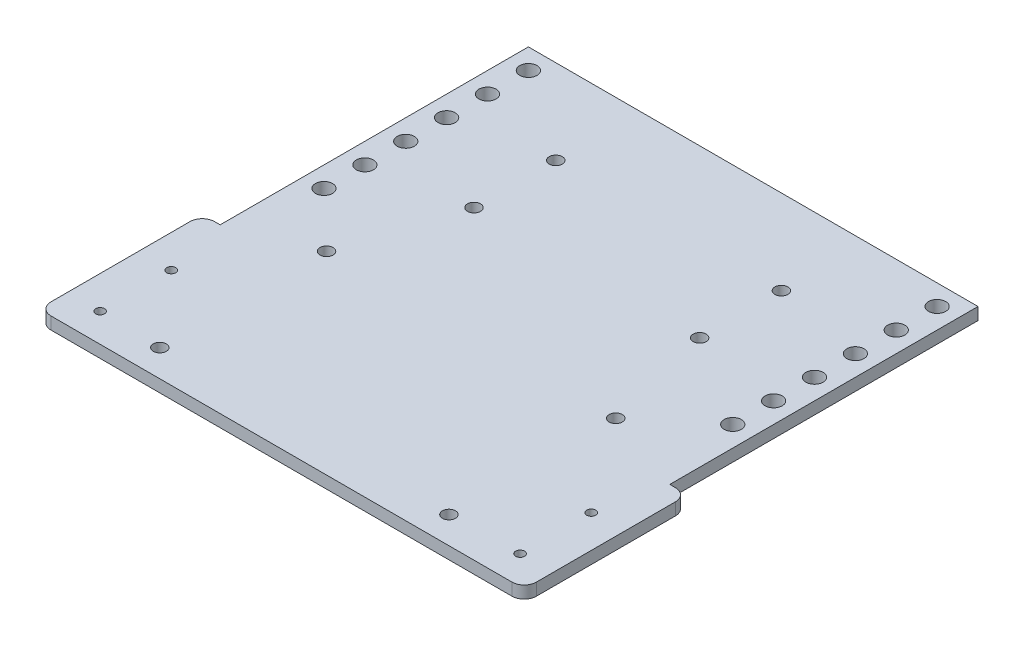
SolidWorks part; units mm, degrees
ref_plane "Alzado" through (0, 0, 0) normal (0, 0, 1) x (1, 0, 0)
ref_plane "Planta" through (0, 0, 0) normal (0, 1, 0) x (1, 0, 0)
ref_plane "Vista lateral" through (0, 0, 0) normal (1, 0, 0) x (0, 0, -1)
sketch "Croquis1" plane through (0, 0, 0) normal (0, 1, 0) x (1, 0, 0)
  line L1 (-95, -57.7) -> (95, -57.7)
  line L2 (-95, -57.7) -> (-95, 57.7)
  line L3 (-95, 57.7) -> (95, 57.7)
  line L4 (95, -57.7) -> (95, 57.7)
  line L5 (0, 57.7) -> (0, -57.7) construction
  line L6 (-95, 0) -> (95, 0) construction
  point P0 (0, 0)
  dimension "D1" = 190
  dimension "D2" = 115.4
extrude "Saliente-Extruir1" add sketch "Croquis1" along normal blind 3
sketch "Croquis2" plane through (0, 3, 0) normal (0, 1, 0) x (1, 0, 0)
  circle A0 centre (-36.375, -51.1) radius 1.6
  circle A1 centre (-36.375, -10.3) radius 1.6
  circle A2 centre (34.375, -10.3) radius 1.6
  circle A3 centre (34.375, -51.1) radius 1.6
  dimension "D1" = 3.2
  dimension "D2" = 3.2
  dimension "D3" = 3.2
  dimension "D4" = 3.2
extrude "Cortar-Extruir1" cut sketch "Croquis2" against normal blind 5
sketch "Croquis4" plane through (0, 3, 0) normal (0, 1, 0) x (1, 0, 0)
  line L0 (-39.375, -54.7) -> (-39.375, -6.7) construction
  line L2 (-95, -57.7) -> (95, -57.7) construction
  line L3 (39.375, -6.7) -> (39.375, -54.7) construction
  circle A0 centre (-51.375, -50.7) radius 1.1
  circle A1 centre (-51.375, -33.3) radius 1.1
  circle A2 centre (51.375, -33.3) radius 1.1
  circle A3 centre (51.375, -50.7) radius 1.1
  dimension "D1" = 17.4
  dimension "D2" = 2.2
  dimension "D3" = 2.2
  dimension "D4" = 12
  dimension "D5" = 7
  dimension "D7" = 12
  dimension "D8" = 12
  dimension "D9" = 17.4
  dimension "D10" = 7
  dimension "D11" = 2.2
  dimension "D12" = 2.2
  dimension "D6" = 12
extrude "Cortar-Extruir3" cut sketch "Croquis4" against normal blind 5
sketch "Croquis5" plane through (0, 3, 0) normal (0, 1, 0) x (1, 0, 0)
  line L1 (-95, -57.7) -> (-59.375, -57.7)
  line L2 (-95, -57.7) -> (-95, -17.7)
  line L3 (-95, -17.7) -> (-59.375, -17.7)
  line L4 (-59.375, -57.7) -> (-59.375, -17.7)
  line L5 (95, -57.7) -> (59.375, -57.7)
  line L6 (95, -57.7) -> (95, -17.7)
  line L7 (95, -17.7) -> (59.375, -17.7)
  line L8 (59.375, -57.7) -> (59.375, -17.7)
  line L9 (-95, 57.7) -> (-55, 57.7)
  line L10 (-95, 57.7) -> (-95, -17.7)
  line L11 (-95, -17.7) -> (-55, -17.7)
  line L12 (-55, 57.7) -> (-55, -17.7)
  line L13 (95, 57.7) -> (55, 57.7)
  line L14 (95, 57.7) -> (95, -17.7)
  line L15 (95, -17.7) -> (55, -17.7)
  line L16 (55, 57.7) -> (55, -17.7)
  circle A0 centre (-51.375, -33.3) radius 1.1 construction
  circle A1 centre (51.375, -33.3) radius 1.1 construction
  line M15 (95, -57.7) -> (95, 57.7)
  line M16 (95, 57.7) -> (-95, 57.7)
  line M17 (-95, 57.7) -> (-95, -57.7)
  line M18 (-95, -57.7) -> (95, -57.7)
  dimension "D2" = 8
  dimension "D1" = 8
  dimension "D3" = 40
  dimension "D4" = 40
  dimension "D5" = 40
  dimension "D6" = 40
extrude "Cortar-Extruir4" cut sketch "Croquis5" against normal blind 5 contours L4 L3 M18 M17 | L12 L3 L11 M16 M17 | L8 L7 M18 M15 | L16 L15 L7 M16 M15
fillet "Redondeo1" radius 3 1 edges at (59.375, 1.5, 17.7)
fillet "Redondeo2" radius 3 1 edges at (-59.375, 1.5, 17.7)
fillet "Redondeo3" radius 3 1 edges at (-59.375, 1.5, 57.7)
fillet "Redondeo4" radius 3 1 edges at (59.375, 1.5, 57.7)
sketch "Croquis6" plane through (0, 3, 0) normal (0, 1, 0) x (1, 0, 0)
  line L0 (55, 57.7) -> (-55, 57.7) construction
  line L1 (55, 57.7) -> (55, -17.7) construction
  line L6 (-55, 57.7) -> (-55, -17.7) construction
  circle A0 centre (50, 52.7) radius 2.1
  circle A4 centre (-50, 52.7) radius 2.1
  circle A8 centre (-50, 42.7) radius 2.1
  circle A9 centre (50, 42.7) radius 2.1
  circle A10 centre (-50, 32.7) radius 2.1
  circle A11 centre (50, 32.7) radius 2.1
  circle A12 centre (-50, 22.7) radius 2.1
  circle A13 centre (50, 22.7) radius 2.1
  circle A14 centre (-50, 12.7) radius 2.1
  circle A15 centre (50, 12.7) radius 2.1
  circle A16 centre (-50, 2.7) radius 2.1
  circle A17 centre (50, 2.7) radius 2.1
  circle A18 centre (-50, 42.7) radius 2.1
  circle A19 centre (50, 42.7) radius 2.1
  circle A20 centre (-50, 32.7) radius 2.1
  circle A21 centre (50, 32.7) radius 2.1
  circle A22 centre (-50, 22.7) radius 2.1
  circle A23 centre (50, 22.7) radius 2.1
  circle A24 centre (-50, 12.7) radius 2.1
  circle A25 centre (50, 12.7) radius 2.1
  dimension "D3" = 2
  dimension "D4" = 4.2
  dimension "D5" = 5
  dimension "D6" = 5
  dimension "D10" = 5
  dimension "D11" = 4.2
  dimension "D18" = 5
  dimension "D22" = 5
sketch "Croquis7" plane through (0, 3, 0) normal (0, 1, 0) x (1, 0, 0)
  circle A0 centre (27.6, 17) radius 1.6
  circle A1 centre (-27.6, 17) radius 1.6
  circle A2 centre (-27.6, 37) radius 1.6
  circle A3 centre (27.6, 37) radius 1.6
extrude "Cortar-Extruir6" cut sketch "Croquis7" against normal blind 10
extrude "Cortar-Extruir7" cut sketch "Croquis6" against normal blind 3 contours A16 | A14 | A12 | A10 | A8 | A4 | A17 | A15 | A13 | A11 | A9 | A0
